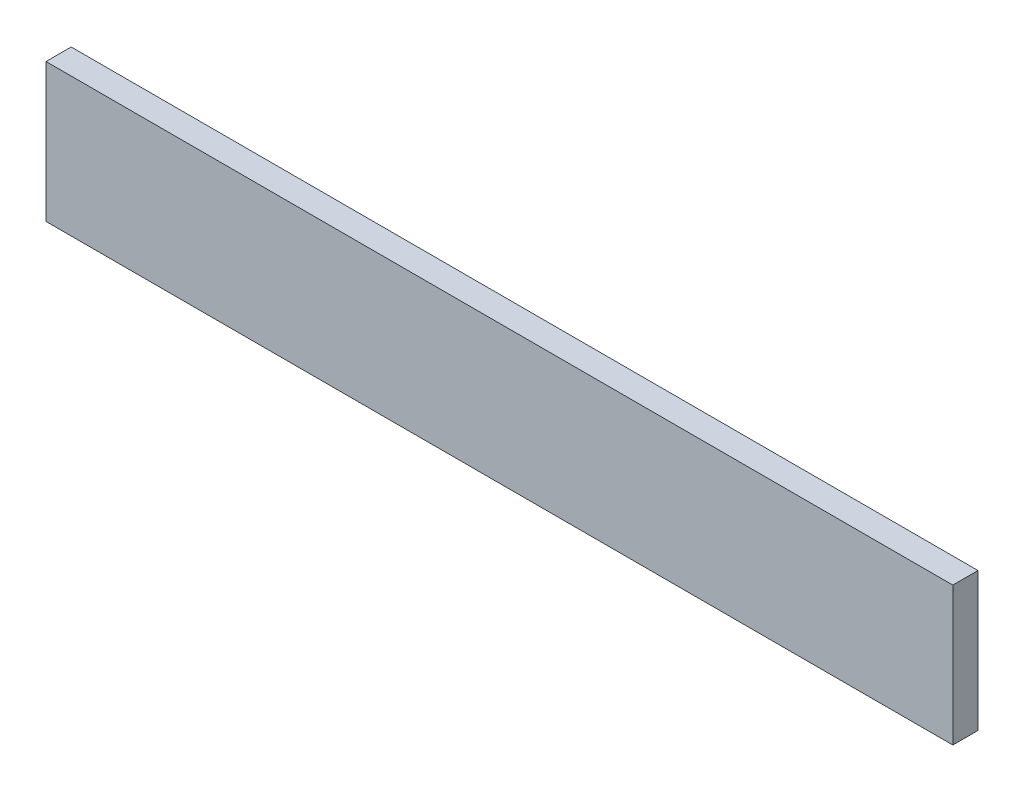
SolidWorks part; units mm, degrees
ref_plane "Front Plane" through (0, 0, 0) normal (0, 0, 1) x (1, 0, 0)
ref_plane "Top Plane" through (0, 0, 0) normal (0, 1, 0) x (1, 0, 0)
ref_plane "Right Plane" through (0, 0, 0) normal (1, 0, 0) x (0, 0, -1)
sketch "Sketch2" plane through (0, 0, 0) normal (0, 0, 1) x (1, 0, 0)
  line L1 (228.6, 34.925) -> (-228.6, 34.925)
  line L2 (228.6, 34.925) -> (228.6, -34.925)
  line L3 (228.6, -34.925) -> (-228.6, -34.925)
  line L4 (-228.6, 34.925) -> (-228.6, -34.925)
  line L5 (228.6, 34.925) -> (-228.6, -34.925) construction
  line L6 (228.6, -34.925) -> (-228.6, 34.925) construction
  point P0 (0, 0)
  dimension "D1" = 69.85
  dimension "D2" = 457.2
extrude "Boss-Extrude1" add sketch "Sketch2" along normal blind 12.7 contours L1 L4 L3 L2
